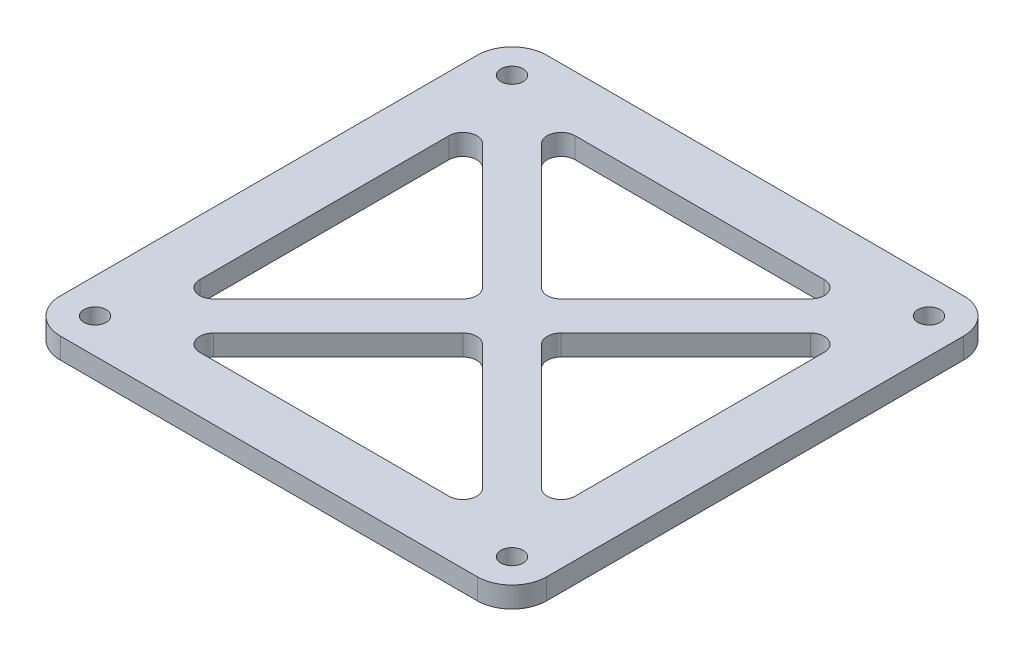
SolidWorks part; units mm, degrees
material "Thornel Mat VMA"
ref_plane "前视基准面" through (0, 0, 0) normal (0, 0, 1) x (1, 0, 0)
ref_plane "上视基准面" through (0, 0, 0) normal (0, 1, 0) x (1, 0, 0)
ref_plane "右视基准面" through (0, 0, 0) normal (1, 0, 0) x (0, 0, -1)
other "Configuration Table"
sketch "草图1" plane through (0, 0, 0) normal (0, 1, 0) x (1, 0, 0)
  line L1 (30, -30) -> (-30, -30) construction
  line L2 (30, -30) -> (30, 30) construction
  line L3 (30, 30) -> (-30, 30) construction
  line L4 (-30, -30) -> (-30, 30) construction
  line L5 (30, -30) -> (-30, 30) construction
  line L6 (30, 30) -> (-30, -30) construction
  line L7 (35, -35) -> (-35, -35)
  line L8 (35, -35) -> (35, 35)
  line L9 (35, 35) -> (-35, 35)
  line L10 (-35, -35) -> (-35, 35)
  line L11 (35, -35) -> (-35, 35) construction
  line L12 (35, 35) -> (-35, -35) construction
  circle A0 centre (-30, 30) radius 1.6
  circle A1 centre (30, 30) radius 1.6
  circle A2 centre (30, -30) radius 1.6
  circle A3 centre (-30, -30) radius 1.6
  point P0 (0, 0)
  point P7 (0, 0)
  point P21 (0, 0)
  dimension "D2" = 3.2
  dimension "D1" = 60
  dimension "D3" = 5
  dimension "D4" = 4
extrude "凸台-拉伸1" add sketch "草图1" along normal blind 3
fillet "圆角1" radius 5 4 edges at (35, 1.5, 35) (35, 1.5, -35) (-35, 1.5, -35) (-35, 1.5, 35)
sketch "草图2" plane through (0, 3, 0) normal (0, 1, 0) x (1, 0, 0)
  line L0 (29.1213, -24.8787) -> (-24.8787, 29.1213)
  line L1 (27, -27) -> (-27, -27)
  line L2 (27, -27) -> (27, 27)
  line L3 (27, 27) -> (-27, 27)
  line L4 (-27, -27) -> (-27, 27)
  line L5 (27, -27) -> (-27, 27) construction
  line L6 (27, 27) -> (-27, -27) construction
  line L7 (24.8787, 29.1213) -> (-29.1213, -24.8787)
  line L8 (24.8787, -29.1213) -> (-29.1213, 24.8787)
  line L9 (29.1213, 24.8787) -> (-24.8787, -29.1213)
  circle A0 centre (30, 30) radius 1.6 construction
  point P0 (0, 0)
  dimension "D1" = 3
  dimension "D2" = 3
  dimension "D3" = 3
extrude "切除-拉伸2" cut sketch "草图2" against normal through all contours L7 L3 L0
fillet "圆角2" radius 2 3 edges at (22.7574, 1.5, -27) (0, 1.5, -4.2426) (-22.7574, 1.5, -27)
sketch "草图3" plane through (0, 0, 0) normal (0, 0, 1) x (1, 0, 0)
  line L0 (0, 0) -> (0, 19.6015) construction
  line L1 (-30, 0) -> (30, 0) construction
pattern_circular "阵列(圆周)1" count 4 over 360 about axis through (0, 0, 0) along (0, 1, 0) of "圆角2", "切除-拉伸2"
